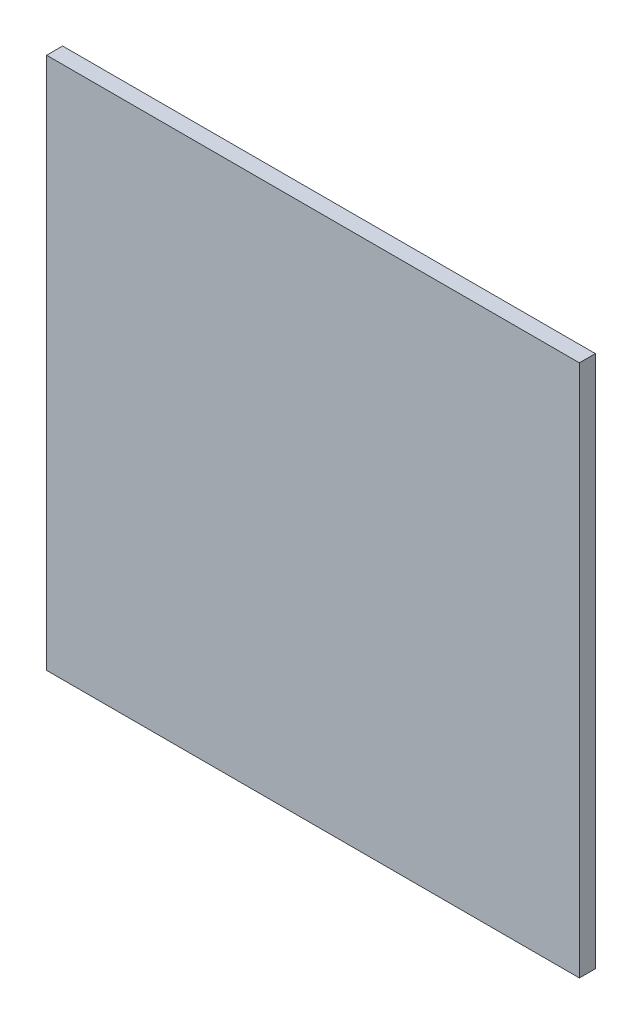
SolidWorks part; units mm, degrees
ref_plane "Front Plane" through (0, 0, 0) normal (1, 0, 0) x (0, 1, 0)
ref_plane "Top Plane" through (0, 0, 0) normal (0, 0, 1) x (0, 1, 0)
ref_plane "Right Plane" through (0, 0, 0) normal (0, 1, 0) x (-1, 0, 0)
sketch "Sketch2" plane through (0, 0, 0) normal (0, 0, 1) x (0, 1, 0)
  line L1 (-50, 50) -> (50, 50)
  line L2 (-50, 50) -> (-50, -50)
  line L3 (-50, -50) -> (50, -50)
  line L4 (50, 50) -> (50, -50)
  line L5 (-50, 50) -> (50, -50) construction
  line L6 (-50, -50) -> (50, 50) construction
  point P0 (0, 0)
  dimension "D1" = 100
  dimension "D2" = 100
extrude "Boss-Extrude1" add sketch "Sketch2" along normal blind 3
